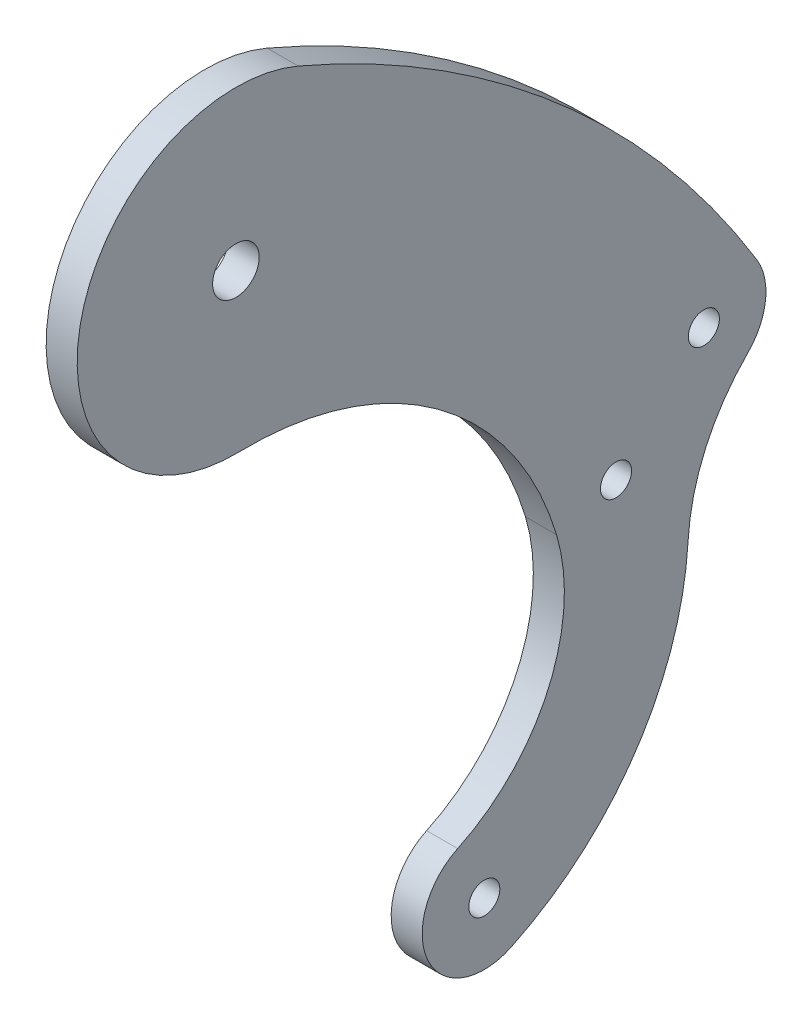
SolidWorks part; units mm, degrees
ref_plane "Front Plane" through (0, 0, 0) normal (0, 0, 1) x (1, 0, 0)
ref_plane "Top Plane" through (0, 0, 0) normal (0, 1, 0) x (1, 0, 0)
ref_plane "Right Plane" through (0, 0, 0) normal (1, 0, 0) x (0, 0, -1)
sketch "Sketch1" plane through (0, 0, 0) normal (1, 0, 0) x (0, 0, -1)
  line L0 (0, 0) -> (8.9803, 8.9803) construction
  line L1 (0, 0) -> (29.1581, 0) construction
  line L2 (8.9803, 8.9803) -> (17.9605, 17.9605) construction
  line L3 (0, 0) -> (-26.9408, -26.9408) construction
  line L4 (-26.9408, -51.0708) -> (-26.9408, -60.5958) construction
  line L5 (-26.9408, -26.9408) -> (-9.8783, -44.0033) construction
  line L6 (-9.8783, -44.0033) -> (-5.3882, -48.4934) construction
  line L7 (-5.3882, -48.4934) -> (47.3609, 4.2557) construction
  line L8 (-8.9803, 8.9803) -> (8.9803, 26.9408)
  line L9 (17.9605, 17.9605) -> (26.9408, 8.9803) construction
  circle A0 centre (0, 0) radius 3.175
  circle A1 centre (8.9803, 8.9803) radius 3.175 construction
  circle A2 centre (17.9605, 17.9605) radius 3.175
  circle A3 centre (-26.9408, -26.9408) radius 24.13 construction
  circle A4 centre (-26.9408, -60.5958) radius 3.175
  circle A5 centre (-26.9408, -26.9408) radius 6.35 construction
  arc A6 (26.9408, 8.9803) -> (8.9803, 26.9408) centre (17.9605, 17.9605) ccw
  arc A7 (-8.9803, 8.9803) -> (-12.1666, -3.6419) centre (0, 0) ccw
  arc A8 (-32.3874, -49.123) -> (-21.4941, -72.0685) centre (-26.9408, -60.5958) ccw
  arc A9 (-12.1666, -3.6419) -> (-32.3874, -49.123) centre (-48.7768, -14.6007) cw
  arc A10 (14.7335, -18.2518) -> (-21.4941, -72.0685) centre (-48.7768, -14.6007) cw
  arc A11 (26.9408, 8.9803) -> (14.7335, -18.2518) centre (56.5784, -20.6574) ccw
  dimension "D1" = 45
  dimension "D2" = 12.7
  dimension "D3" = 6.35
  dimension "D4" = 48.26
  dimension "D7" = 12.7
  dimension "D9" = 12.7
  dimension "D10" = 12.7
  dimension "D11" = 38.2152
  dimension "D5" = 38.1
  dimension "D6" = 9.525
  dimension "D8" = 6.35
extrude "Boss-Extrude1" add sketch "Sketch1" along normal blind 6.35
sketch "Sketch2" plane through (6.35, 0, 0) normal (1, 0, 0) x (0, 0, -1)
  line L0 (-9.0202, 98.7429) -> (-84.8371, 22.926) construction
  line L1 (8.9803, 26.9408) -> (-8.9803, 8.9803) construction
  line L2 (-8.9803, 8.9803) -> (8.9803, 26.9408) construction
  line L3 (-8.9803, 8.9803) -> (8.9803, 26.9408)
  circle A0 centre (-77.7408, 75.9292) radius 32.4611 construction
  arc A1 (-12.1666, -3.6419) -> (-76.9956, 43.4767) centre (-75.4787, -22.5936) ccw
  arc A2 (-32.3874, -49.123) -> (-12.1666, -3.6419) centre (-48.7768, -14.6007) ccw construction
  arc A3 (28.808, 24.5652) -> (-65.0005, 105.7857) centre (-144.7518, -81.1099) ccw
  arc A4 (26.9408, 8.9803) -> (8.9803, 26.9408) centre (17.9605, 17.9605) ccw construction
  arc A5 (-65.0005, 105.7857) -> (-76.9956, 43.4767) centre (-77.7408, 75.9292) ccw
  arc A6 (-8.9803, 8.9803) -> (-12.1666, -3.6419) centre (0, 0) ccw construction
  arc A7 (-8.9803, 8.9803) -> (-12.1666, -3.6419) centre (0, 0) ccw
  arc A8 (28.808, 24.5652) -> (8.9803, 26.9408) centre (17.9605, 17.9605) ccw
  circle A9 centre (-77.7408, 75.9292) radius 4.7625
  dimension "D4" = 203.2
  dimension "D5" = 9.525
  dimension "D1" = 63.5
  dimension "D3" = 50.8
  dimension "D6" = 136.525
extrude "Boss-Extrude2" add sketch "Sketch2" against normal up to surface (6.35 mm away) up to face at (0, -14.5423, 2.1881)
